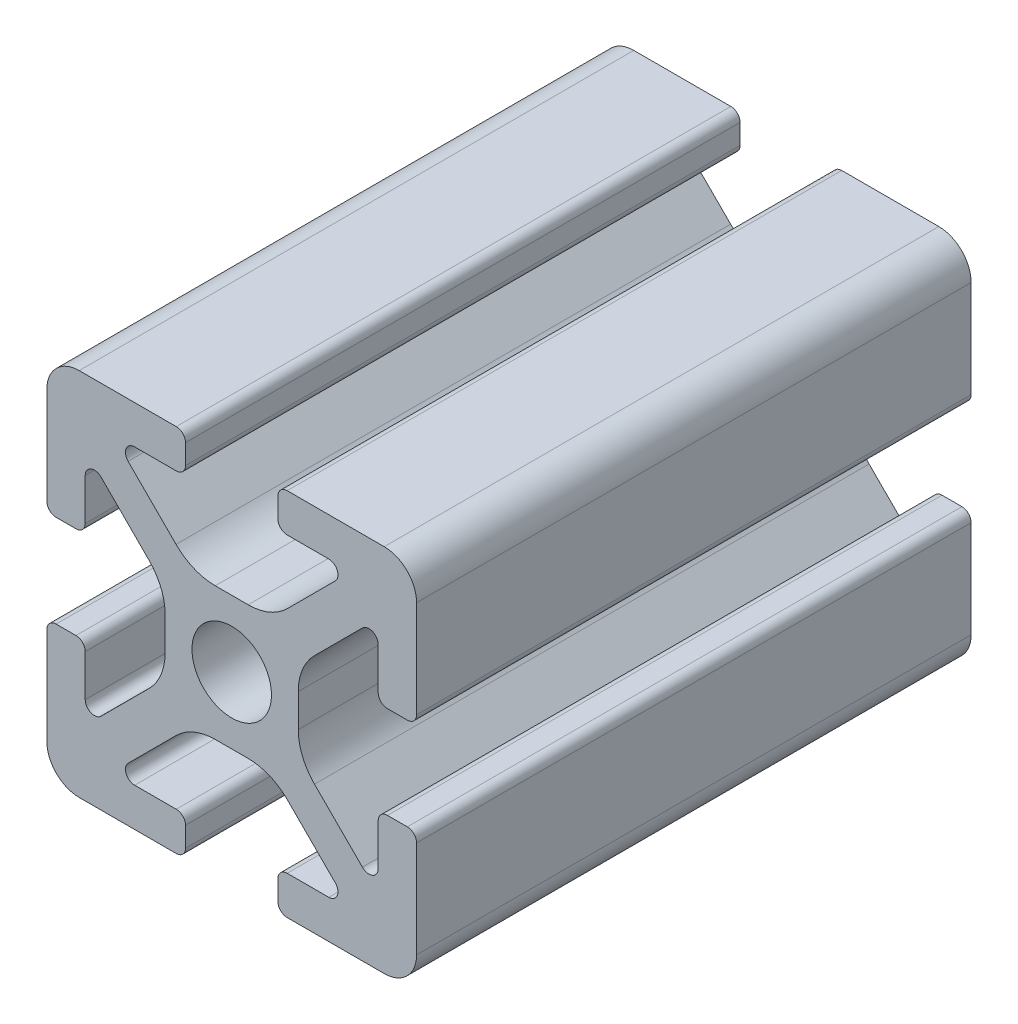
SolidWorks part; units mm, degrees
ref_plane "Front Plane" through (0, 0, 0) normal (0, 0, 1) x (1, 0, 0)
ref_plane "Top Plane" through (0, 0, 0) normal (0, 1, 0) x (1, 0, 0)
ref_plane "Right Plane" through (0, 0, 0) normal (1, 0, 0) x (0, 0, -1)
sketch "Sketch2" plane through (0, 0, 0) normal (0, 0, 1) x (1, 0, 0)
  line L0 (0, 10) -> (0, -10) construction
  line L1 (-10, 0) -> (10, 0) construction
  line L2 (2.5, -10) -> (10, -10)
  line L3 (10, -10) -> (10, -2.5)
  line L4 (2.5, -10) -> (2.5, -7.9246)
  line L5 (2.5, -7.9246) -> (6.4571, -7.9246)
  line L6 (6.4571, -7.9246) -> (2.1325, -3.6)
  line L7 (0, 0) -> (10, -10) construction
  line L8 (10, -2.5) -> (7.9246, -2.5)
  line L9 (7.9246, -2.5) -> (7.9246, -6.4571)
  line L10 (7.9246, -6.4571) -> (3.6, -2.1325)
  line L11 (5.7623, -4.2948) -> (4.2948, -5.7623) construction
  circle A0 centre (0, 0) radius 2.15
  arc A1 (5.25, -7.9246) -> (5.6036, -7.0711) centre (5.25, -7.4246) ccw construction
  point P8 (0, -3.6)
  point P16 (5.0286, -5.0286)
  dimension "Center Hole Diameter" = 4.3
  dimension "D3" = 0.5
  dimension "Rail Height" = 20
  dimension "Rail Width" = 20
  dimension "T-Slot Width" = 5
  dimension "Slot Depth" = 6.4
  dimension "Slot Inner Width" = 11.5
sketch "Sketch3" plane through (0, 0, 0) normal (1, 0, 0) x (0, 0, -1)
  line L0 (-76.2, -10) -> (76.2, -10) construction
  line L1 (-50.8, 0) -> (50.8, 0) construction
  line L2 (0, 10) -> (0, -10) construction
  line L3 (0, 10) -> (0, -10) construction
  point P6 (-50.8, 0)
  point P8 (50.8, 0)
  dimension "D1" = 25.4
  dimension "Length" = 152.4
sketch "Sketch4" plane through (0, 0, 0) normal (0, 0, 1) x (1, 0, 0)
  line L0 (3, -10) -> (8.25, -10)
  line L1 (2.5, -10) -> (10, -10) construction
  line L2 (2.5, -10) -> (2.5, -7.9246) construction
  line L3 (2.5, -7.9246) -> (6.4571, -7.9246) construction
  line L4 (2.5, -8.4246) -> (2.5, -9.5)
  line L5 (3, -7.9246) -> (5.25, -7.9246)
  line L6 (0, -3.6) -> (0.8898, -3.6)
  line L7 (6.4571, -7.9246) -> (2.1325, -3.6) construction
  line L8 (3.0112, -4.4787) -> (5.6036, -7.0711)
  line L9 (10, -10) -> (10, -2.5) construction
  line L10 (7.9246, -6.4571) -> (3.6, -2.1325) construction
  line L11 (7.9246, -2.5) -> (7.9246, -6.4571) construction
  line L12 (7.9246, -5.25) -> (7.9246, -3)
  line L13 (10, -2.5) -> (7.9246, -2.5) construction
  line L14 (8.4246, -2.5) -> (9.5, -2.5)
  line L15 (10, -3) -> (10, -8.25)
  line L16 (7.0711, -5.6036) -> (4.4787, -3.0112)
  line L17 (3.6, 0) -> (3.6, -0.8898)
  line L18 (-10, 0) -> (10, 0) construction
  line L19 (0, -3.6) -> (0, -2.15)
  line L20 (0, 10) -> (0, -10) construction
  line L21 (3.6, 0) -> (2.15, 0)
  arc A0 (2.5, -9.5) -> (3, -10) centre (3, -9.5) ccw
  arc A1 (5.25, -7.9246) -> (5.6036, -7.0711) centre (5.25, -7.4246) ccw construction
  arc A2 (2.5, -8.4246) -> (3, -7.9246) centre (3, -8.4246) cw
  arc A3 (5.25, -7.9246) -> (5.6036, -7.0711) centre (5.25, -7.4246) ccw
  arc A4 (0.8898, -3.6) -> (3.0112, -4.4787) centre (0.8898, -6.6) cw
  arc A5 (8.25, -10) -> (10, -8.25) centre (8.25, -8.25) ccw
  arc A6 (7.0711, -5.6036) -> (7.9246, -5.25) centre (7.4246, -5.25) ccw
  arc A7 (7.9246, -3) -> (8.4246, -2.5) centre (8.4246, -3) cw
  arc A8 (9.5, -2.5) -> (10, -3) centre (9.5, -3) cw
  arc A9 (4.4787, -3.0112) -> (3.6, -0.8898) centre (6.6, -0.8898) cw
  circle A10 centre (0, 0) radius 2.15 construction
  arc A11 (0, -2.15) -> (2.15, 0) centre (0, 0) ccw
  dimension "D1" = 1.75
  dimension "D2" = 3
extrude "Boss-Extrude1" add sketch "Sketch4" along normal mid plane 30
mirror "Mirror1" about plane through (0, 0, 0) normal (1, 0, 0) of bodies 134
mirror "Mirror2" about plane through (0, 0, 0) normal (0, 1, 0) of bodies 135
equation "\"D3@Sketch2\"=\"T-Slot Width@Sketch2\"*0.1"
equation "\"D1@Sketch4\"=\"D3@Sketch2\"*3.5"
equation "\"D2@Sketch4\"=\"D3@Sketch2\"*6"
equation "\"D1@Boss-Extrude1\"=110"
